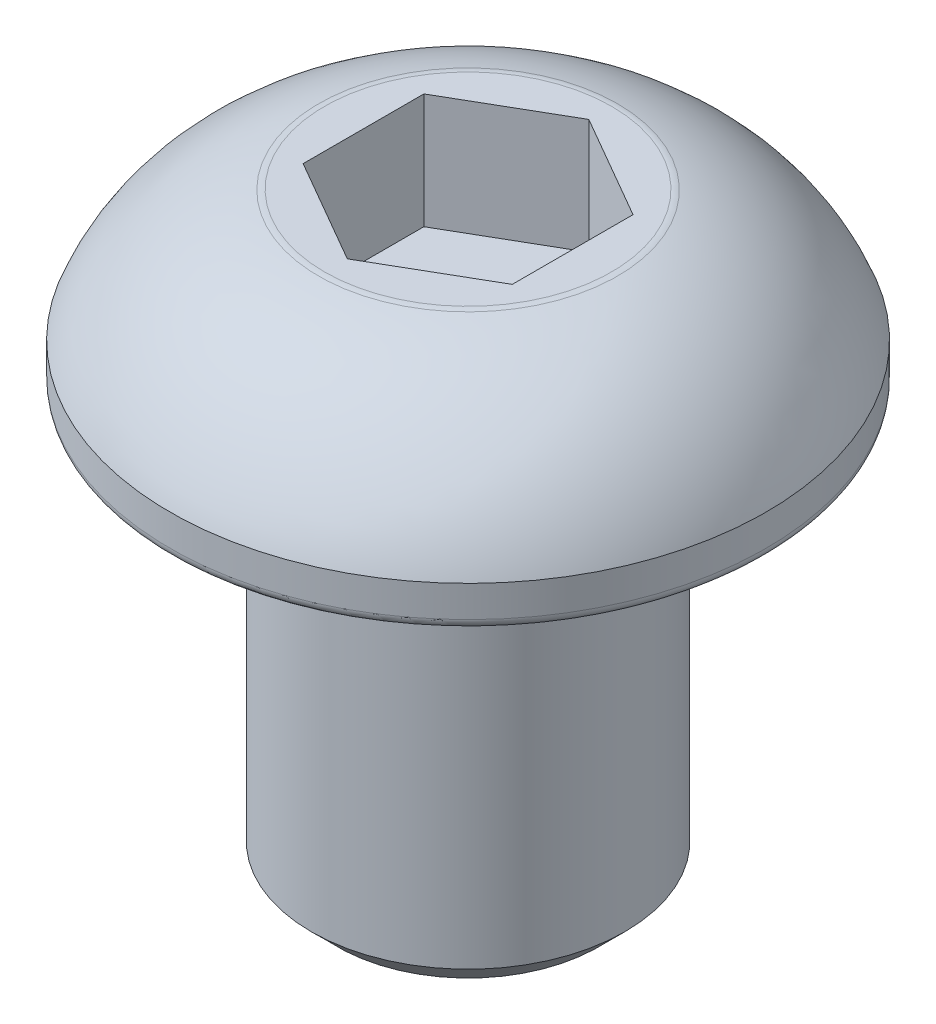
SolidWorks part; units mm, degrees
material "ASTM A36 Steel"
ref_plane "Front Plane" through (0, 0, 0) normal (0, 0, 1) x (1, 0, 0)
ref_plane "Top Plane" through (0, 0, 0) normal (0, 1, 0) x (1, 0, 0)
ref_plane "Right Plane" through (0, 0, 0) normal (1, 0, 0) x (0, 0, -1)
sketch "Sketch1" plane through (0, 0, 0) normal (0, 0, 1) x (1, 0, 0)
  line L7 (-1.5, -0.1) -> (-1.5, -3.75)
  line L8 (-1.25, -4) -> (0, -4)
  line L9 (0, -4) -> (0, 1.65)
  line L10 (-1.6, 0) -> (-2.75, 0)
  line L11 (-2.85, 0.1) -> (-2.85, 0.4)
  line L12 (-1.3725, 1.65) -> (0, 1.65)
  line L13 (-1.5, -3.75) -> (-1.25, -4)
  arc A0 (-2.85, 0.4) -> (-1.4287, 1.6436) centre (-0.9784, -0.3051) cw
  arc A3 (-2.75, 0) -> (-2.85, 0.1) centre (-2.75, 0.1) cw
  arc A4 (-1.4287, 1.6436) -> (-1.3725, 1.65) centre (-1.3725, 1.4) cw
  arc A5 (-1.5, -0.1) -> (-1.6, 0) centre (-1.6, -0.1) ccw
  point P1 (-1.5, -4)
  point P21 (-1.4, 1.65)
  point P24 (-1.5, 0)
  dimension "D1" = 1.5
  dimension "D7" = 2
  dimension "D8" = 0.1
  dimension "D9" = 0.25
  dimension "D10" = 0.1
  dimension "D2" = 2.85
  dimension "D4" = 1.4
  dimension "D5" = 1.65
  dimension "D6" = 0.4
  dimension "D11" = 4
revolve "Revolve1" add sketch "Sketch1" angle 360 about L9
sketch "Sketch2" plane through (0, 1.65, 0) normal (0, 1, 0) x (1, 0, 0)
  line L1 (-1, 0.5774) -> (-1, -0.5774)
  line L2 (-1, -0.5774) -> (0, -1.1547)
  line L3 (0, -1.1547) -> (1, -0.5774)
  line L4 (1, -0.5774) -> (1, 0.5774)
  line L5 (1, 0.5774) -> (0, 1.1547)
  line L6 (0, 1.1547) -> (-1, 0.5774)
  circle A0 centre (0, 0) radius 1 construction
  dimension "D1" = 2
extrude "Cut-Extrude1" cut sketch "Sketch2" against normal blind 1.1
